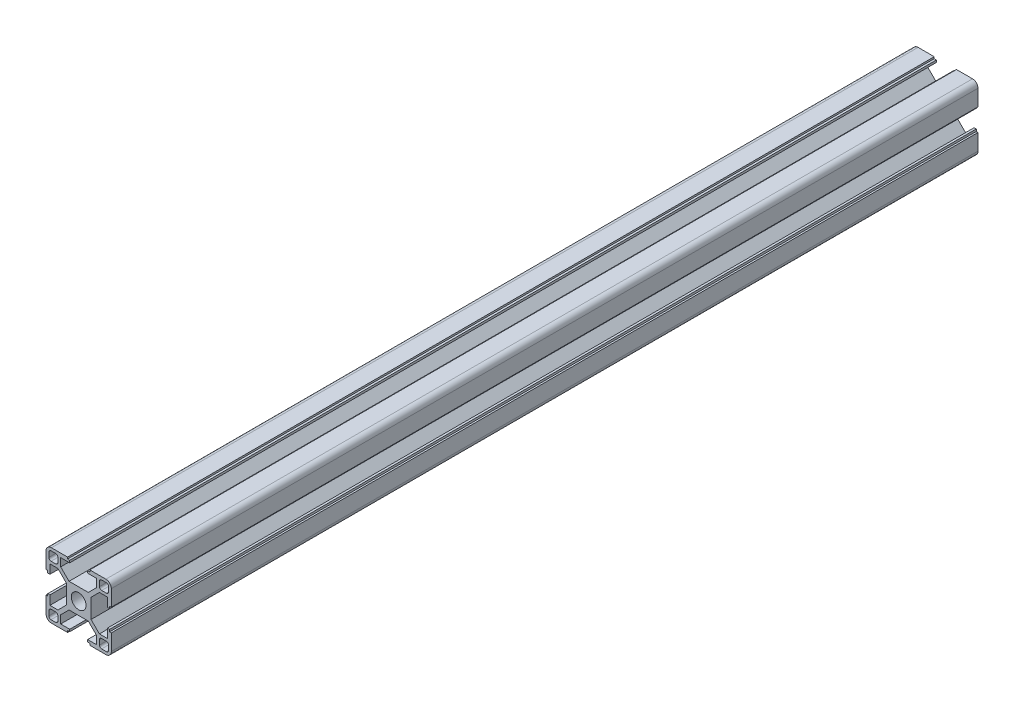
SolidWorks part; units mm, degrees
material "6061-T6 (SS)"
ref_plane "前视基准面" through (0, 0, 0) normal (0, 0, 1) x (1, 0, 0)
ref_plane "上视基准面" through (0, 0, 0) normal (0, 1, 0) x (1, 0, 0)
ref_plane "右视基准面" through (0, 0, 0) normal (1, 0, 0) x (0, 0, -1)
sketch "Sketch1" plane through (0, 0, 0) normal (0, 0, 1) x (1, 0, 0)
  line L0 (-5.1, 15) -> (-5.1, 14.2)
  line L1 (-12.5, -15) -> (12.5, -15)
  line L2 (-15, -12.5) -> (-15, 12.5)
  line L3 (-12.5, 15) -> (12.5, 15)
  line L4 (15, -12.5) -> (15, 12.5)
  line L5 (-15, -15) -> (15, 15) construction
  line L6 (-15, 15) -> (15, -15) construction
  line L7 (-5.1, 14.2) -> (-4.1, 14.2)
  line L8 (-4.1, 14.2) -> (-4.1, 13.2)
  line L9 (-4.1, 13.2) -> (-8.25, 13.2)
  line L10 (-8.25, 13.2) -> (-8.25, 9.5228)
  line L11 (-8.25, 9.5228) -> (-4.4272, 5.7)
  line L12 (-4.4272, 5.7) -> (4.4272, 5.7)
  line L13 (-5.1, 15) -> (5.1, 15)
  line L14 (0, 15) -> (0, 5.7) construction
  line L15 (8.25, 9.5228) -> (4.4272, 5.7)
  line L16 (8.25, 13.2) -> (8.25, 9.5228)
  line L17 (4.1, 13.2) -> (8.25, 13.2)
  line L18 (4.1, 14.2) -> (4.1, 13.2)
  line L19 (5.1, 14.2) -> (4.1, 14.2)
  line L20 (5.1, 15) -> (5.1, 14.2)
  line L21 (15, 5.1) -> (14.2, 5.1)
  line L22 (14.2, 5.1) -> (14.2, 4.1)
  line L23 (14.2, 4.1) -> (13.2, 4.1)
  line L24 (13.2, 4.1) -> (13.2, 8.25)
  line L25 (13.2, 8.25) -> (9.5228, 8.25)
  line L26 (9.5228, 8.25) -> (5.7, 4.4272)
  line L27 (5.7, 4.4272) -> (5.7, -4.4272)
  line L28 (15, 5.1) -> (15, -5.1)
  line L29 (9.5228, -8.25) -> (5.7, -4.4272)
  line L30 (13.2, -8.25) -> (9.5228, -8.25)
  line L31 (13.2, -4.1) -> (13.2, -8.25)
  line L32 (14.2, -4.1) -> (13.2, -4.1)
  line L33 (14.2, -5.1) -> (14.2, -4.1)
  line L34 (15, -5.1) -> (14.2, -5.1)
  line L35 (15, 0) -> (5.7, 0) construction
  line L36 (5.1, -15) -> (5.1, -14.2)
  line L37 (5.1, -14.2) -> (4.1, -14.2)
  line L38 (4.1, -14.2) -> (4.1, -13.2)
  line L39 (4.1, -13.2) -> (8.25, -13.2)
  line L40 (8.25, -13.2) -> (8.25, -9.5228)
  line L41 (8.25, -9.5228) -> (4.4272, -5.7)
  line L42 (4.4272, -5.7) -> (-4.4272, -5.7)
  line L43 (5.1, -15) -> (-5.1, -15)
  line L44 (-8.25, -9.5228) -> (-4.4272, -5.7)
  line L45 (-8.25, -13.2) -> (-8.25, -9.5228)
  line L46 (-4.1, -13.2) -> (-8.25, -13.2)
  line L47 (-4.1, -14.2) -> (-4.1, -13.2)
  line L48 (-5.1, -14.2) -> (-4.1, -14.2)
  line L49 (-5.1, -15) -> (-5.1, -14.2)
  line L50 (0, -15) -> (0, -5.7) construction
  line L51 (-15, -5.1) -> (-14.2, -5.1)
  line L52 (-14.2, -5.1) -> (-14.2, -4.1)
  line L53 (-14.2, -4.1) -> (-13.2, -4.1)
  line L54 (-13.2, -4.1) -> (-13.2, -8.25)
  line L55 (-13.2, -8.25) -> (-9.5228, -8.25)
  line L56 (-9.5228, -8.25) -> (-5.7, -4.4272)
  line L57 (-5.7, -4.4272) -> (-5.7, 4.4272)
  line L58 (-15, -5.1) -> (-15, 5.1)
  line L59 (-9.5228, 8.25) -> (-5.7, 4.4272)
  line L60 (-13.2, 8.25) -> (-9.5228, 8.25)
  line L61 (-13.2, 4.1) -> (-13.2, 8.25)
  line L62 (-14.2, 4.1) -> (-13.2, 4.1)
  line L63 (-14.2, 5.1) -> (-14.2, 4.1)
  line L64 (-15, 5.1) -> (-14.2, 5.1)
  line L65 (-15, 0) -> (-5.7, 0) construction
  line L66 (0, 0) -> (0, 5.7) construction
  circle A0 centre (0, 0) radius 3.4
  arc A1 (-12.5, -15) -> (-15, -12.5) centre (-12.5, -12.5) cw
  arc A2 (12.5, -15) -> (15, -12.5) centre (12.5, -12.5) ccw
  arc A3 (12.5, 15) -> (15, 12.5) centre (12.5, 12.5) cw
  arc A4 (-15, 12.5) -> (-12.5, 15) centre (-12.5, 12.5) cw
  point P0 (0, 0)
  dimension "D3" = 6.8
  dimension "D12" = 2.5
  dimension "D1" = 30
  dimension "D2" = 30
  dimension "D4" = 16.5
  dimension "D5" = 8.2
  dimension "D6" = 10.2
  dimension "D7" = 7.5
  dimension "D9" = 1.8
  dimension "D10" = 1.8
  dimension "D11" = 0.8
  dimension "D8" = 4
extrude "Extrude1" add sketch "Sketch1" along normal blind 398 contours A4 L2 L64 L63 L62 L61 L60 L59 L57 L56 L55 L54 L53 L52 L51 A1 L1 L49 L48 L47 L46 L45 L44 L42 L41 L40 L39 L38 L37 L36 A2 L4 L34 L33 L32 L31 L30 L29 L27 L26 L25 L24 L23 L22 L21 A3 L3 L20
sketch "Sketch2" plane through (0, 0, 398) normal (0, 0, 1) x (1, 0, 0)
  line L0 (13.7, 12.7) -> (13.7, 10.55)
  line L1 (-12.7, 13.7) -> (-10.55, 13.7)
  line L2 (-13.7, 12.7) -> (-13.7, 10.55)
  line L3 (-12.7, 9.55) -> (-10.55, 9.55)
  line L4 (-9.55, 12.7) -> (-9.55, 10.55)
  line L5 (-13.7, 13.7) -> (-9.55, 9.55) construction
  line L6 (-13.7, 9.55) -> (-9.55, 13.7) construction
  line L7 (12.7, 13.7) -> (10.55, 13.7)
  line L8 (9.55, 12.7) -> (9.55, 10.55)
  line L9 (12.7, 9.55) -> (10.55, 9.55)
  line L10 (12.7, -13.7) -> (10.55, -13.7)
  line L11 (13.7, -12.7) -> (13.7, -10.55)
  line L12 (12.7, -9.55) -> (10.55, -9.55)
  line L13 (9.55, -12.7) -> (9.55, -10.55)
  line L14 (-13.7, -12.7) -> (-13.7, -10.55)
  line L15 (-12.7, -13.7) -> (-10.55, -13.7)
  line L16 (-9.55, -12.7) -> (-9.55, -10.55)
  line L17 (-12.7, -9.55) -> (-10.55, -9.55)
  line L18 (0, 0) -> (-9.55, 9.55) construction
  line L19 (-12.5, 15) -> (-5.1, 15) construction
  line L20 (-15, 5.1) -> (-15, 12.5) construction
  line L21 (-13.2, 8.25) -> (-9.5228, 8.25) construction
  line L22 (-8.25, 13.2) -> (-8.25, 9.5228) construction
  arc A0 (-13.7, -12.7) -> (-12.7, -13.7) centre (-12.7, -12.7) ccw
  arc A1 (-10.55, -13.7) -> (-9.55, -12.7) centre (-10.55, -12.7) ccw
  arc A2 (-9.55, -10.55) -> (-10.55, -9.55) centre (-10.55, -10.55) ccw
  arc A3 (-13.7, -10.55) -> (-12.7, -9.55) centre (-12.7, -10.55) cw
  arc A4 (13.7, -10.55) -> (12.7, -9.55) centre (12.7, -10.55) ccw
  arc A5 (12.7, -13.7) -> (13.7, -12.7) centre (12.7, -12.7) ccw
  arc A6 (10.55, -13.7) -> (9.55, -12.7) centre (10.55, -12.7) cw
  arc A7 (10.55, -9.55) -> (9.55, -10.55) centre (10.55, -10.55) ccw
  arc A8 (13.7, 12.7) -> (12.7, 13.7) centre (12.7, 12.7) ccw
  arc A9 (13.7, 10.55) -> (12.7, 9.55) centre (12.7, 10.55) cw
  arc A10 (9.55, 10.55) -> (10.55, 9.55) centre (10.55, 10.55) ccw
  arc A11 (10.55, 13.7) -> (9.55, 12.7) centre (10.55, 12.7) ccw
  arc A12 (-10.55, 13.7) -> (-9.55, 12.7) centre (-10.55, 12.7) cw
  arc A13 (-10.55, 9.55) -> (-9.55, 10.55) centre (-10.55, 10.55) ccw
  arc A14 (-13.7, 10.55) -> (-12.7, 9.55) centre (-12.7, 10.55) ccw
  arc A15 (-12.7, 13.7) -> (-13.7, 12.7) centre (-12.7, 12.7) ccw
  point P0 (-11.625, 11.625)
  dimension "D2" = 1
  dimension "D3" = 1.3
  dimension "D4" = 1.3
  dimension "D5" = 1.3
  dimension "D6" = 1.3
  dimension "D1" = 4
extrude "Extrude2" cut sketch "Sketch2" against normal through all
